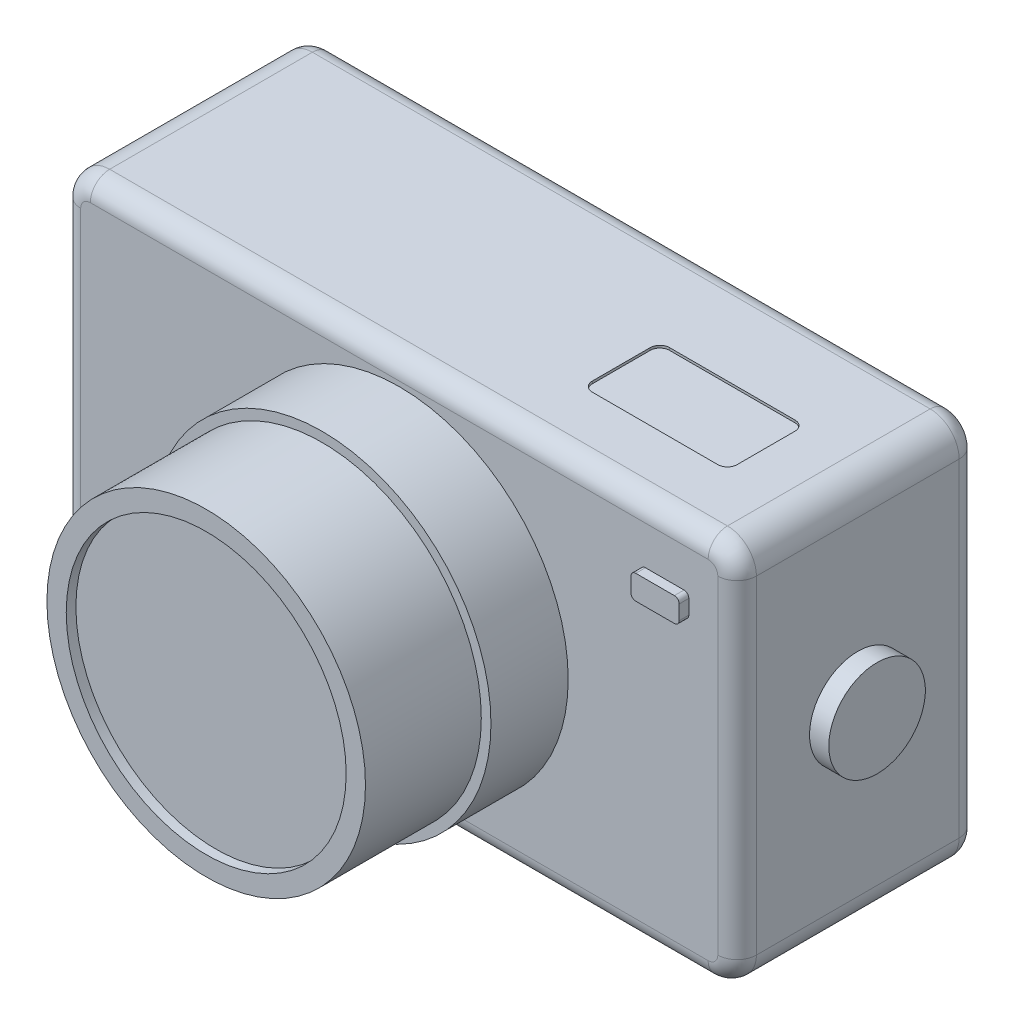
SolidWorks part; units mm, degrees
ref_plane "Front Plane" through (0, 0, 0) normal (0, 0, 1) x (1, 0, 0)
ref_plane "Top Plane" through (0, 0, 0) normal (0, 1, 0) x (1, 0, 0)
ref_plane "Right Plane" through (0, 0, 0) normal (1, 0, 0) x (0, 0, -1)
sketch "Sketch1" plane through (0, 0, 0) normal (0, 0, 1) x (1, 0, 0)
  line L1 (-32, -20) -> (32, -20)
  line L2 (-35, -17) -> (-35, 17)
  line L3 (-32, 20) -> (32, 20)
  line L4 (35, -17) -> (35, 17)
  line L5 (-35, -20) -> (35, 20) construction
  line L6 (-35, 20) -> (35, -20) construction
  arc A0 (-35, 17) -> (-32, 20) centre (-32, 17) cw
  arc A1 (-32, -20) -> (-35, -17) centre (-32, -17) cw
  arc A2 (32, -20) -> (35, -17) centre (32, -17) ccw
  arc A3 (32, 20) -> (35, 17) centre (32, 17) cw
  point P0 (0, 0)
  dimension "D3" = 3
  dimension "D1" = 40
  dimension "D2" = 70
extrude "Boss-Extrude1" add sketch "Sketch1" along normal blind 25
fillet "Fillet1" radius 2 16 edges at (34.1213, 19.1213, 25) (35, 0, 25) (34.1213, -19.1213, 25) (0, -20, 25) (-34.1213, -19.1213, 25) (-35, 0, 25) (-34.1213, 19.1213, 25) (34.1213, 19.1213, 0) (35, 0, 0) (34.1213, -19.1213, 0) (0, -20, 0) (-34.1213, -19.1213, 0) (-35, 0, 0) (-34.1213, 19.1213, 0) (0, 20, 25) (0, 20, 0)
sketch "Sketch2" plane through (0, 0, 25) normal (0, 0, 1) x (1, 0, 0)
  circle A0 centre (0, 0) radius 17.5
  dimension "D1" = 35
extrude "Boss-Extrude2" add sketch "Sketch2" along normal blind 8
sketch "Sketch3" plane through (0, 0, 33) normal (0, 0, 1) x (1, 0, 0)
  circle A0 centre (0, 0) radius 16.5
  dimension "D1" = 33
extrude "Boss-Extrude3" add sketch "Sketch3" along normal blind 12
sketch "Sketch4" plane through (0, 0, 45) normal (0, 0, 1) x (1, 0, 0)
  circle A0 centre (0, 0) radius 14.5
  dimension "D1" = 29
extrude "Cut-Extrude1" cut sketch "Sketch4" against normal blind 2
sketch "Sketch5" plane through (0, 0, 43) normal (0, 0, 1) x (1, 0, 0)
  circle A2 centre (0, 0) radius 16.5 construction
  circle A3 centre (0, 0) radius 16.5
extrude "Boss-Extrude4" add sketch "Sketch5" along normal blind 1
sketch "Sketch6" plane through (0, 0, 0) normal (0, 0, -1) x (-1, 0, 0)
  line L0 (0, 0) -> (0, 37.2436) construction
  line L1 (0, 0) -> (-68.3103, 0) construction
  line L2 (0, 0) -> (-32, 17) construction
  circle A0 centre (-25, 13.2813) radius 2.5
  circle A1 centre (25, 13.2813) radius 2.5
  circle A2 centre (25, -13.2812) radius 2.5
  circle A3 centre (-25, -13.2813) radius 2.5
  dimension "D1" = 5
  dimension "D2" = 25
extrude "Cut-Extrude2" cut sketch "Sketch6" against normal blind 0.75
sketch "Sketch7" plane through (0, 0, 0.75) normal (0, 0, -1) x (-1, 0, 0)
  line L0 (-24.6, 15.749) -> (-24.6, 13.6813)
  line L1 (-24.6, 13.6813) -> (-22.5322, 13.6813)
  line L2 (-22.5322, 12.8813) -> (-24.6, 12.8812)
  line L3 (-24.6, 12.8812) -> (-24.6, 10.8135)
  line L4 (-25.4, 10.8135) -> (-25.4, 12.8813)
  line L5 (-25.4, 12.8813) -> (-27.4678, 12.8813)
  line L6 (-27.4678, 13.6813) -> (-25.4, 13.6813)
  line L7 (-25.4, 13.6813) -> (-25.4, 15.749)
  line L8 (-24.6, 13.6813) -> (-25.4, 12.8813) construction
  line L9 (-25.4, 13.6813) -> (-24.6, 12.8812) construction
  line L10 (-43.9285, 0) -> (0, 0) construction
  line L11 (0, 0) -> (0, 53.7903) construction
  line L12 (25.4, 13.6813) -> (24.6, 12.8812) construction
  line L13 (24.6, 13.6813) -> (25.4, 12.8813) construction
  line L14 (25.4, 13.6813) -> (25.4, 15.749)
  line L15 (27.4678, 13.6813) -> (25.4, 13.6813)
  line L16 (25.4, 12.8813) -> (27.4678, 12.8813)
  line L17 (25.4, 10.8135) -> (25.4, 12.8813)
  line L18 (24.6, 12.8812) -> (24.6, 10.8135)
  line L19 (22.5322, 12.8813) -> (24.6, 12.8812)
  line L20 (24.6, 13.6813) -> (22.5322, 13.6813)
  line L21 (24.6, 15.749) -> (24.6, 13.6813)
  line L22 (24.6, -13.6813) -> (25.4, -12.8813) construction
  line L23 (25.4, -13.6813) -> (24.6, -12.8812) construction
  line L24 (24.6, -15.749) -> (24.6, -13.6813)
  line L25 (24.6, -13.6813) -> (22.5322, -13.6813)
  line L26 (22.5322, -12.8813) -> (24.6, -12.8812)
  line L27 (24.6, -12.8812) -> (24.6, -10.8135)
  line L28 (25.4, -10.8135) -> (25.4, -12.8813)
  line L29 (25.4, -12.8813) -> (27.4678, -12.8813)
  line L30 (27.4678, -13.6813) -> (25.4, -13.6813)
  line L31 (25.4, -13.6813) -> (25.4, -15.749)
  line L32 (-25.4, -13.6813) -> (-24.6, -12.8812) construction
  line L33 (-24.6, -13.6813) -> (-25.4, -12.8813) construction
  line L34 (-25.4, -13.6813) -> (-25.4, -15.749)
  line L35 (-27.4678, -13.6813) -> (-25.4, -13.6813)
  line L36 (-25.4, -12.8813) -> (-27.4678, -12.8813)
  line L37 (-25.4, -10.8135) -> (-25.4, -12.8813)
  line L38 (-24.6, -12.8812) -> (-24.6, -10.8135)
  line L39 (-22.5322, -12.8813) -> (-24.6, -12.8812)
  line L40 (-24.6, -13.6813) -> (-22.5322, -13.6813)
  line L41 (-24.6, -15.749) -> (-24.6, -13.6813)
  circle A0 centre (-25, 13.2813) radius 2.5 construction
  arc A1 (-24.6, 15.749) -> (-25.4, 15.749) centre (-25, 13.2813) ccw
  arc A2 (-22.5322, 12.8813) -> (-22.5322, 13.6813) centre (-25, 13.2813) ccw
  arc A3 (-25.4, 10.8135) -> (-24.6, 10.8135) centre (-25, 13.2813) ccw
  arc A4 (-27.4678, 13.6813) -> (-27.4678, 12.8813) centre (-25, 13.2813) ccw
  arc A5 (27.4678, 13.6813) -> (27.4678, 12.8813) centre (25, 13.2813) cw
  arc A6 (25.4, 10.8135) -> (24.6, 10.8135) centre (25, 13.2813) cw
  arc A7 (22.5322, 12.8813) -> (22.5322, 13.6813) centre (25, 13.2813) cw
  arc A8 (24.6, 15.749) -> (25.4, 15.749) centre (25, 13.2813) cw
  arc A9 (24.6, -15.749) -> (25.4, -15.749) centre (25, -13.2813) ccw
  arc A10 (22.5322, -12.8813) -> (22.5322, -13.6813) centre (25, -13.2813) ccw
  arc A11 (25.4, -10.8135) -> (24.6, -10.8135) centre (25, -13.2813) ccw
  arc A12 (27.4678, -13.6813) -> (27.4678, -12.8813) centre (25, -13.2813) ccw
  arc A13 (-27.4678, -13.6813) -> (-27.4678, -12.8813) centre (-25, -13.2813) cw
  arc A14 (-25.4, -10.8135) -> (-24.6, -10.8135) centre (-25, -13.2813) cw
  arc A15 (-22.5322, -12.8813) -> (-22.5322, -13.6813) centre (-25, -13.2813) cw
  arc A16 (-24.6, -15.749) -> (-25.4, -15.749) centre (-25, -13.2813) cw
  point P18 (-25, 13.2813)
  point P32 (25, 13.2813)
  point P46 (25, -13.2813)
  point P60 (-25, -13.2813)
  dimension "D2" = 0.8
  dimension "D3" = 45
  dimension "D1" = 4
extrude "Cut-Extrude3" cut sketch "Sketch7" against normal blind 0.5
sketch "Sketch8" plane through (0, 20, 0) normal (0, 1, 0) x (1, 0, 0)
  line L0 (32, -23) -> (32, -2) construction
  line L1 (26, -18) -> (13, -18)
  line L2 (27, -17) -> (27, -11)
  line L3 (26, -10) -> (13, -10)
  line L4 (12, -17) -> (12, -11)
  line L5 (27, -18) -> (12, -10) construction
  line L6 (27, -10) -> (12, -18) construction
  line L7 (-32, -23) -> (32, -23) construction
  arc A0 (13, -10) -> (12, -11) centre (13, -11) ccw
  arc A1 (13, -18) -> (12, -17) centre (13, -17) cw
  arc A2 (26, -18) -> (27, -17) centre (26, -17) ccw
  arc A3 (27, -11) -> (26, -10) centre (26, -11) ccw
  point P0 (19.5, -14)
  dimension "D5" = 1
  dimension "D1" = 15
  dimension "D2" = 8
  dimension "D3" = 5
  dimension "D4" = 5
extrude "Cut-Extrude4" cut sketch "Sketch8" against normal blind 0.25
sketch "Sketch11" plane through (-35, 0, 0) normal (-1, 0, 0) x (0, 0, 1)
  line L0 (23, 17) -> (2, 17) construction
  circle A0 centre (12.5, 0) radius 5
  point P5 (12.5, 17)
  dimension "D1" = 10
extrude "Boss-Extrude5" add sketch "Sketch11" along normal blind 2
mirror "Mirror1" about plane through (0, 0, 0) normal (1, 0, 0) of "Boss-Extrude5"
sketch "Sketch12" plane through (0, 0, 25) normal (0, 0, 1) x (1, 0, 0)
  line L5 (32, 18) -> (-32, 18) construction
  line L6 (25.5, 14) -> (29.5, 14)
  line L26 (25, 13.5) -> (25, 12)
  line L27 (25.5, 11.5) -> (29.5, 11.5)
  line L28 (30, 13.5) -> (30, 12)
  line L29 (25, 14) -> (30, 11.5) construction
  line L30 (25, 11.5) -> (30, 14) construction
  line L31 (33, -17) -> (33, 17) construction
  arc A20 (25.5, 14) -> (25, 13.5) centre (25.5, 13.5) ccw
  arc A21 (25, 12) -> (25.5, 11.5) centre (25.5, 12) ccw
  arc A22 (29.5, 11.5) -> (30, 12) centre (29.5, 12) ccw
  arc A23 (29.5, 14) -> (30, 13.5) centre (29.5, 13.5) cw
  point P0 (27.5, 12.75)
  dimension "D5" = 0.5
  dimension "D1" = 4
  dimension "D2" = 3
  dimension "D3" = 2.5
  dimension "D4" = 5
extrude "Boss-Extrude6" add sketch "Sketch12" along normal blind 1
